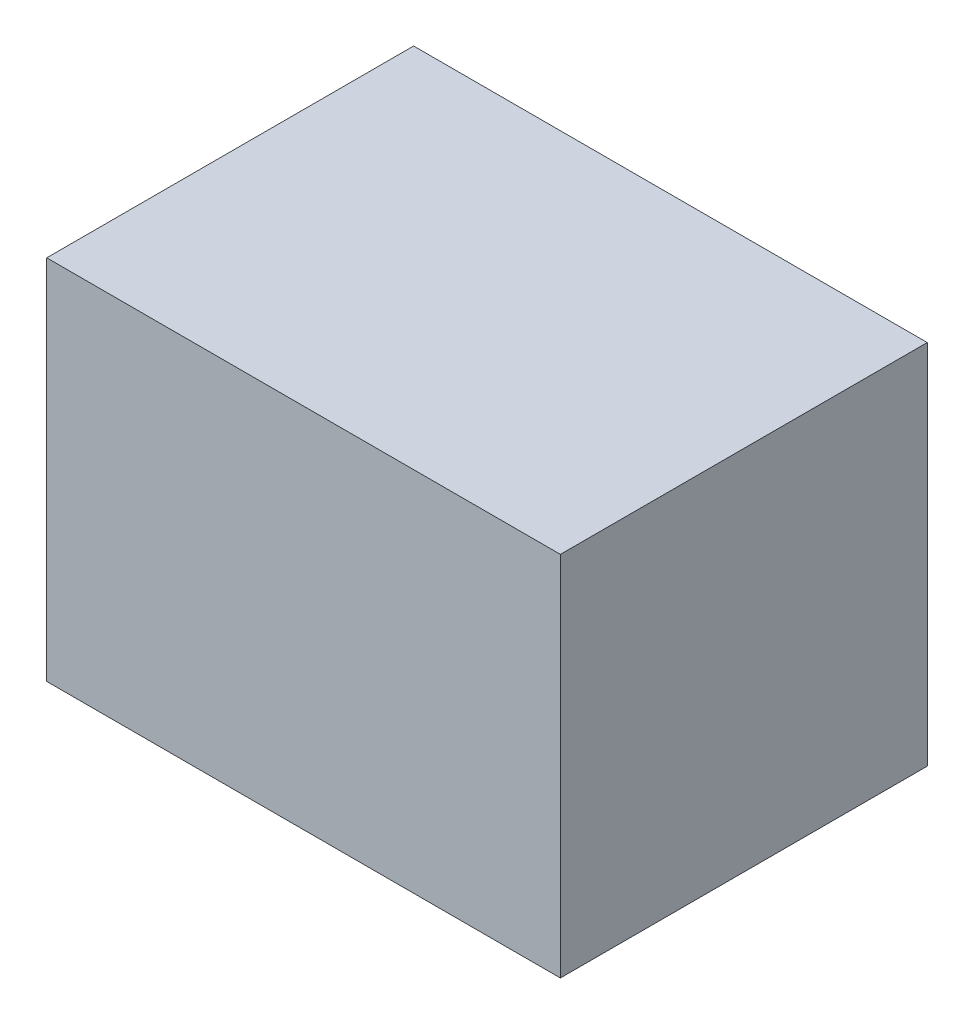
SolidWorks part; units mm, degrees
ref_plane "Front Plane" through (0, 0, 0) normal (0, 0, 1) x (1, 0, 0)
ref_plane "Top Plane" through (0, 0, 0) normal (0, 1, 0) x (1, 0, 0)
ref_plane "Right Plane" through (0, 0, 0) normal (1, 0, 0) x (0, 0, -1)
sketch "Sketch1" plane through (0, 0, 0) normal (1, 0, 0) x (0, 0, -1)
  line L1 (-31.75, 31.75) -> (31.75, 31.75)
  line L2 (-31.75, 31.75) -> (-31.75, -31.75)
  line L3 (-31.75, -31.75) -> (31.75, -31.75)
  line L4 (31.75, 31.75) -> (31.75, -31.75)
  line L5 (-31.75, 31.75) -> (31.75, -31.75) construction
  line L6 (-31.75, -31.75) -> (31.75, 31.75) construction
  point P0 (0, 0)
  dimension "D1" = 63.5
  dimension "D2" = 63.5
extrude "Boss-Extrude1" add sketch "Sketch1" along normal blind 88.9
sketch "Sketch2" plane through (0, 0, 0) normal (-1, 0, 0) x (0, 0, 1)
  circle A0 centre (0, 0) radius 3
extrude "Boss-Extrude2" add sketch "Sketch2" along normal blind 22.225
